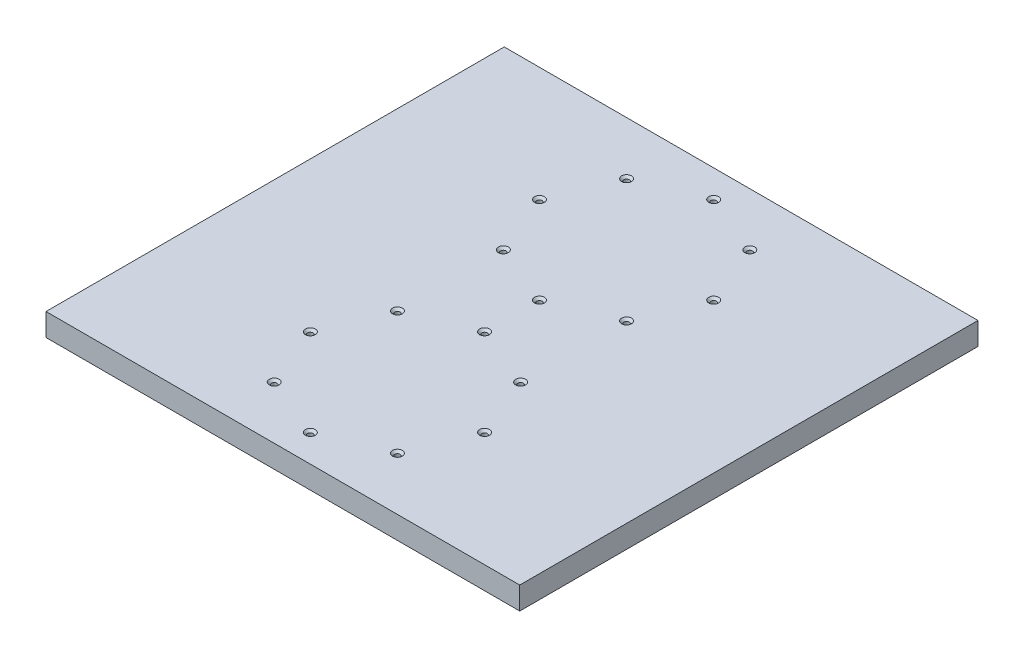
SolidWorks part; units mm, degrees
ref_plane "Front Plane" through (0, 0, 0) normal (0, 0, 1) x (1, 0, 0)
ref_plane "Top Plane" through (0, 0, 0) normal (0, 1, 0) x (1, 0, 0)
ref_plane "Right Plane" through (0, 0, 0) normal (1, 0, 0) x (0, 0, -1)
sketch "Sketch1" plane through (0, 0, 0) normal (0, 1, 0) x (1, 0, 0)
  line L0 (-104.993, 0) -> (0, 0) construction
  line L1 (-104.993, 50.7809) -> (104.993, 50.7809)
  line L2 (-104.993, 50.7809) -> (-104.993, -50.7809)
  line L3 (-104.993, -50.7809) -> (104.993, -50.7809)
  line L4 (104.993, 50.7809) -> (104.993, -50.7809)
  line L5 (0, 0) -> (0, 50.7809) construction
extrude "Boss-Extrude1" add sketch "Sketch1" along normal blind 10
sketch "Sketch2" plane through (0, 10, 0) normal (0, 1, 0) x (1, 0, 0)
  point P0 (-38.6158, 0)
hole_wizard "CSK for M2 Flat Head Machine Screw1" positions "3DSketch1" profile "Sketch3" countersink size "M2" standard "ANSI Metric" end condition through all
sketch3d "3DSketch1"
  point P0 (-38.6158, 10, 0)
sketch "Sketch3" plane through (-38.6158, 10, 0) normal (1, 0, 0) x (0, 0, 1)
  line L0 (0, 0) -> (0, 10)
  line L1 (0, 10) -> (1.2, 10)
  line L2 (1.2, 10) -> (1.2, 1)
  line L3 (1.2, 1) -> (2.2, 0)
  line L5 (2.2, 0) -> (0, 0)
  line L6 (-1.2, 1) -> (-2.2, 0) construction
  line L11 (0, -6.35) -> (0, 107.95) construction
  dimension "Thru Hole Dia." = 2.4
  dimension "Thru Hole Depth" = 10
  dimension "Near C'Sink Dia." = 4.4
  dimension "Near C'Sink Angle" = 90
sketch "Sketch4" plane through (0, 0, 0) normal (1, 0, 0) x (0, 0, -1)
  line L0 (0, -1.0328) -> (0, 26.0735) construction
pattern_circular "CirPattern1" count 8 every 45 about axis through (0, 0, 0) along (0, 1, 0) of "CSK for M2 Flat Head Machine Screw1"
mirror "Mirror1" about plane through (-104.993, 10, -50.7809) normal (0, 0, 1) of "Boss-Extrude1", "CSK for M2 Flat Head Machine Screw1", "CirPattern1"
